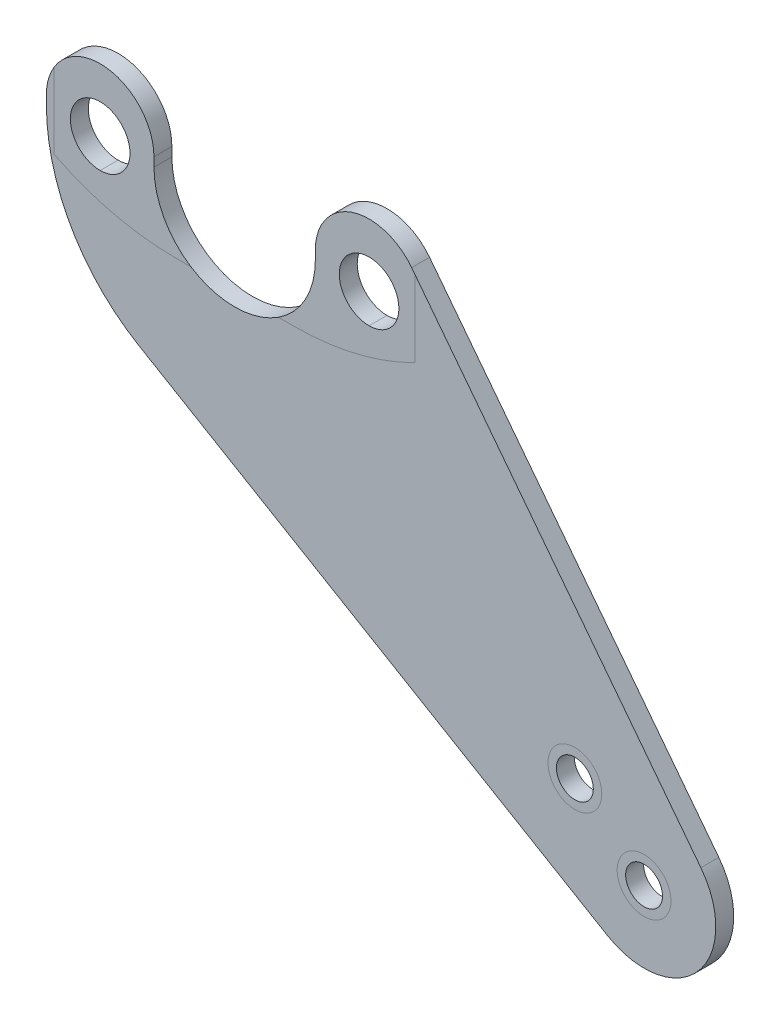
SolidWorks part; units mm, degrees
material "Plain Carbon Steel"
ref_plane "Front Plane" through (0, 0, 0) normal (0, 0, 1) x (1, 0, 0)
ref_plane "Top Plane" through (0, 0, 0) normal (0, 1, 0) x (1, 0, 0)
ref_plane "Right Plane" through (0, 0, 0) normal (1, 0, 0) x (0, 0, -1)
sketch "Sketch1" plane through (0, 0, 0) normal (0, 0, 1) x (1, 0, 0)
  line L0 (-14.2875, 1.5875) -> (-14.2875, 0) construction
  line L1 (14.2875, 0) -> (14.2875, 1.5875) construction
  line L2 (-14.2875, 1.5875) -> (-14.2875, 0)
  line L3 (14.2875, 0) -> (14.2875, 1.5875)
  line L4 (-33.3375, 1.5875) -> (-33.3375, 0)
  line L7 (31.3554, 7.4039) -> (82.5729, -59.0167)
  line L8 (-16.9471, -28.7086) -> (66.0597, -77.7085)
  circle A0 centre (0, 0) radius 14.2875 construction
  arc A1 (-14.2875, 1.5875) -> (-23.8125, 11.1125) centre (-23.8125, 1.5875) ccw construction
  arc A2 (23.8125, 11.1125) -> (14.2875, 1.5875) centre (23.8125, 1.5875) ccw construction
  arc A3 (-14.2875, 0) -> (14.2875, 0) centre (0, 0) ccw
  arc A4 (-14.2875, 1.5875) -> (-33.3375, 1.5875) centre (-23.8125, 1.5875) ccw
  arc A5 (31.3554, 7.4039) -> (14.2875, 1.5875) centre (23.8125, 1.5875) ccw
  circle A6 centre (-23.8125, 0) radius 5.2754 construction
  circle A7 centre (23.8125, 0) radius 5.2754 construction
  circle A8 centre (-23.8125, 0) radius 5.2754
  circle A9 centre (23.8125, 0) radius 5.2754
  circle A10 centre (72.5157, -66.7719) radius 3.2639 construction
  circle A11 centre (60.259, -56.4873) radius 3.2639 construction
  circle A12 centre (72.5157, -66.7719) radius 3.2639
  circle A13 centre (60.259, -56.4873) radius 3.2639
  arc A14 (66.0597, -77.7085) -> (82.5729, -59.0167) centre (72.5157, -66.7719) ccw
  arc A15 (-33.3375, 0) -> (-16.9471, -28.7086) centre (0, 0) ccw
  dimension "D2" = 25.4
extrude "Boss-Extrude1" add sketch "Sketch1" along normal blind 3.175
sketch "Sketch2" plane through (0, 0, 0) normal (0, 0, -1) x (-1, 0, 0)
  line L0 (-24.3417, -14.2875) -> (-31.75, -8.7312) construction
  line L1 (31.75, -8.7312) -> (24.3417, -14.2875) construction
  line L2 (19.5792, -15.875) -> (-19.5792, -15.875) construction
  line L3 (-24.3417, -14.2875) -> (-31.75, -8.7312)
  line L4 (31.75, -8.7312) -> (24.3417, -14.2875)
  line L5 (19.5792, -15.875) -> (-19.5792, -15.875)
  line L6 (-34.925, -2.3812) -> (-34.925, 20.6375) construction
  line L7 (-34.925, -2.3812) -> (-34.925, 20.6375)
  arc A0 (-34.925, -2.3812) -> (-31.75, -8.7312) centre (-26.9875, -2.3812) ccw construction
  arc A1 (-24.3417, -14.2875) -> (-19.5792, -15.875) centre (-19.5792, -7.9375) ccw construction
  arc A2 (31.75, -8.7312) -> (34.925, -2.3812) centre (26.9875, -2.3812) ccw construction
  arc A3 (19.5792, -15.875) -> (24.3417, -14.2875) centre (19.5792, -7.9375) ccw construction
  arc A4 (-34.925, -2.3812) -> (-31.75, -8.7312) centre (-26.9875, -2.3812) ccw
  arc A5 (-24.3417, -14.2875) -> (-19.5792, -15.875) centre (-19.5792, -7.9375) ccw
  arc A6 (31.75, -8.7312) -> (34.925, -2.3812) centre (26.9875, -2.3812) ccw
  arc A7 (19.5792, -15.875) -> (24.3417, -14.2875) centre (19.5792, -7.9375) ccw
split line "Caliper Piston Face"
sketch "Sketch3" plane through (0, 0, 3.175) normal (0, 0, 1) x (1, 0, 0)
  line L0 (-31.95, 6.8676) -> (-31.95, -6.8676) construction
  line L1 (-31.95, 6.8676) -> (-31.95, -6.8676)
  line L2 (31.95, -6.8676) -> (31.95, 6.8676) construction
  line L3 (-10.5471, -12) -> (10.5471, -12) construction
  line L4 (31.95, -6.8676) -> (31.95, 6.8676)
  line L5 (-10.5471, -12) -> (10.5471, -12)
  arc A0 (10.5471, -12) -> (31.95, -6.8676) centre (10.5471, 35.1928) ccw construction
  arc A1 (-31.95, -6.8676) -> (-10.5471, -12) centre (-10.5471, 35.1928) ccw construction
  arc A2 (10.5471, -12) -> (31.95, -6.8676) centre (10.5471, 35.1928) ccw
  arc A3 (-31.95, -6.8676) -> (-10.5471, -12) centre (-10.5471, 35.1928) ccw
split line "Caliper Pad"
sketch "Sketch4" plane through (0, 0, 0) normal (0, 0, -1) x (-1, 0, 0)
  circle A0 centre (-60.259, -56.4873) radius 4.7625
  circle A1 centre (-72.5157, -66.7719) radius 4.7625
  dimension "D1" = 9.525
split line "Mounting Bolts"
ref_plane "Force" through (0, 0, 0) normal (-1, 0, 0) x (0, 0, 1)
ref_plane "VWall 2" through (0, 0, 3.175) normal (0, 0, 1) x (1, 0, 0)
sketch "Sketch5" plane through (0, 0, 0) normal (0, 0, -1) x (-1, 0, 0)
  line L0 (-23.8125, 5.2754) -> (-23.8125, -5.2754)
  line L1 (23.8125, 5.2754) -> (23.8125, -5.2754)
  circle A0 centre (-23.8125, 0) radius 5.2754 construction
  circle A1 centre (23.8125, 0) radius 5.2754 construction
split line "Split Line1"
ref_plane "Plane3" through (23.8125, 0, 0) normal (-1, 0, 0) x (0, 0, 1)
